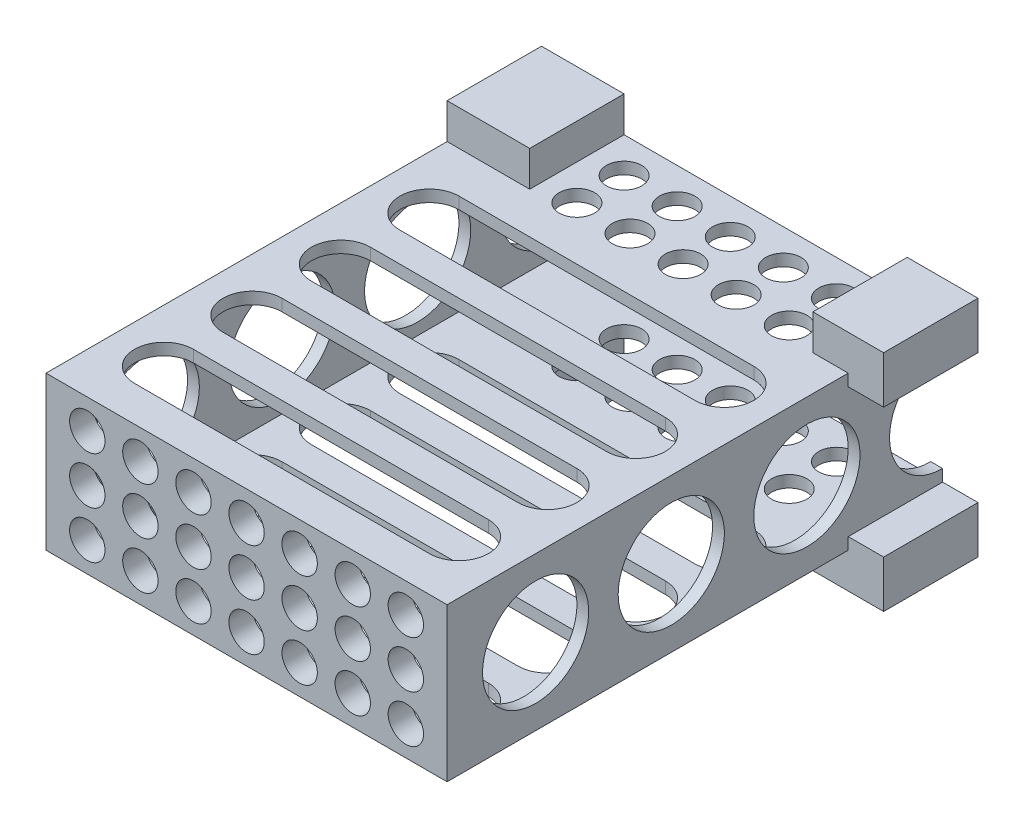
SolidWorks part; units mm, degrees
ref_plane "Přední rovina" through (0, 0, 0) normal (0, 0, 1) x (1, 0, 0)
ref_plane "Horní rovina" through (0, 0, 0) normal (0, 1, 0) x (1, 0, 0)
ref_plane "Pravá rovina" through (0, 0, 0) normal (1, 0, 0) x (0, 0, -1)
sketch "Skica1" plane through (0, 0, 0) normal (0, 0, 1) x (1, 0, 0)
  line L0 (0, 0) -> (0, 13) construction
  line L1 (0, 0) -> (34, 0) construction
  line L2 (-34, 13) -> (34, 13)
  line L3 (34, 13) -> (34, -13)
  line L4 (-34, -13) -> (34, -13)
  line L5 (-34, 13) -> (-34, -13)
  point P9 (0, -13)
  dimension "D1" = 68
  dimension "D2" = 26
extrude "Přidat vysunutím1" add sketch "Skica1" along normal blind 4
sketch "Skica2" plane through (0, 0, 0) normal (0, 0, -1) x (-1, 0, 0)
  line L0 (0, 0) -> (32, 0) construction
  line L1 (0, 0) -> (0, 11) construction
  line L2 (-32, 11) -> (32, 11)
  line L3 (32, 11) -> (32, -11)
  line L4 (-32, 11) -> (-32, -11)
  line L5 (-32, -11) -> (32, -11)
  line L6 (34, 13) -> (-34, 13)
  line L7 (-34, 13) -> (-34, -13)
  line L8 (-34, -13) -> (34, -13)
  line L9 (34, -13) -> (34, 13)
  point P11 (-32, 0)
  dimension "D1" = 2
  dimension "D2" = 2
extrude "Přidat vysunutím2" add sketch "Skica2" along normal blind 80
sketch "Skica7" plane through (0, 0, -80) normal (0, 0, 1) x (1, 0, 0)
  line L4 (0, 0) -> (34, 0) construction
  line L5 (32, 11) -> (34, 11) construction
  line L14 (3, 19) -> (40, 19)
  line L15 (40, 19) -> (40, 11)
  line L16 (40, 11) -> (34, 11)
  line L17 (34, 13) -> (34, -13) construction
  line L18 (34, 11) -> (34, 13)
  line L20 (3, 19) -> (-34, 19)
  line L21 (-34, 19) -> (-34, 13)
  line L22 (-32, 11) -> (32, 11) construction
  line L23 (34, 13) -> (-34, 13)
  line L25 (-34, -19) -> (-34, -13)
  line L26 (3, -19) -> (40, -19)
  line L27 (34, -13) -> (-34, -13)
  line L28 (34, -11) -> (34, -13)
  line L29 (40, -11) -> (34, -11)
  line L30 (40, -19) -> (40, -11)
  line L31 (3, -19) -> (-34, -19)
  dimension "D1" = 8
  dimension "D2" = 6
extrude "Přidat vysunutím9" add sketch "Skica7" along normal blind 16
sketch "Skica3" plane through (0, 0, -80) normal (0, 0, -1) x (-1, 0, 0)
  line L0 (0, 0) -> (-36, 0) construction
  line L1 (-36, 0) -> (-36, 15) construction
  line L2 (-4, 0) -> (-4, 15) construction
  circle A4 centre (-36, 15) radius 2
  circle A5 centre (28, 15) radius 2
  circle A6 centre (28, -15) radius 2
  circle A7 centre (-36, -15) radius 2
  dimension "D3" = 4
  dimension "D4" = 4
  dimension "D1" = 36
  dimension "D2" = 15
extrude "Odebrat vysunutím1" cut sketch "Skica3" against normal blind 15
sketch "Skica4" plane through (0, -13, 0) normal (0, -1, 0) x (1, 0, 0)
  line L0 (0, 0) -> (0, -52) construction
  line L1 (0, -52) -> (25, -52) construction
  line L2 (-25, -57) -> (25, -57)
  line L8 (-25, -47) -> (25, -47)
  line L9 (-25, -32) -> (25, -32)
  line L10 (-25, -42) -> (25, -42)
  line L11 (-25, -17) -> (25, -17)
  line L12 (-25, -27) -> (25, -27)
  line L13 (-25, -2) -> (25, -2)
  line L14 (-25, -12) -> (25, -12)
  arc A0 (25, -57) -> (25, -47) centre (25, -52) ccw
  arc A3 (-25, -57) -> (-25, -47) centre (-25, -52) cw
  arc A4 (25, -42) -> (25, -32) centre (25, -37) ccw
  arc A5 (-25, -42) -> (-25, -32) centre (-25, -37) cw
  arc A6 (25, -27) -> (25, -17) centre (25, -22) ccw
  arc A7 (-25, -27) -> (-25, -17) centre (-25, -22) cw
  arc A8 (25, -12) -> (25, -2) centre (25, -7) ccw
  arc A9 (-25, -12) -> (-25, -2) centre (-25, -7) cw
  dimension "D3" = 10
  dimension "D5" = 15
  dimension "D4" = 4
  dimension "D1" = 52
  dimension "D2" = 25
extrude "Odebrat vysunutím2" cut sketch "Skica4" against normal through all
sketch "Skica5" plane through (-34, 0, 0) normal (-1, 0, 0) x (0, 0, 1)
  line L0 (0, 0) -> (-80, 0) construction
  line L1 (-80, -19) -> (-80, 19) construction
  circle A0 centre (-80, 0) radius 9
  circle A1 centre (-57, 0) radius 9
  circle A2 centre (-34, 0) radius 9
  circle A3 centre (-11, 0) radius 9
  dimension "D1" = 18
  dimension "D3" = 23
  dimension "D2" = 4
extrude "Odebrat vysunutím3" cut sketch "Skica5" against normal through all
sketch "Skica8" plane through (0, 0, -80) normal (0, 0, -1) x (-1, 0, 0)
  line L0 (20, 19) -> (20, 13)
  line L1 (-40, 19) -> (34, 19) construction
  line L3 (20, 13) -> (-28, 13)
  line L5 (-28, 13) -> (-28, 19)
  line L6 (-28, 19) -> (20, 19)
  line L7 (0, 0) -> (14.4774, 0) construction
  line L8 (-28, -13) -> (-28, -19)
  line L9 (20, -13) -> (-28, -13)
  line L10 (20, -19) -> (20, -13)
  line L11 (-28, -19) -> (20, -19)
  line L12 (32, 11) -> (-32, 11) construction
  circle A0 centre (28, 15) radius 2 construction
  circle A1 centre (-36, 15) radius 2 construction
  dimension "D1" = 8
  dimension "D2" = 8
  dimension "D3" = 2
extrude "Odebrat vysunutím4" cut sketch "Skica8" against normal blind 16
sketch "Skica9" plane through (0, 0, 4) normal (0, 0, 1) x (1, 0, 0)
  line L0 (0, 0) -> (-27, 0) construction
  line L1 (-27, 0) -> (-27, 8) construction
  circle A0 centre (-27, 8) radius 3
  circle A1 centre (-18, 8) radius 3
  circle A2 centre (-9, 8) radius 3
  circle A3 centre (0, 8) radius 3
  circle A4 centre (9, 8) radius 3
  circle A5 centre (18, 8) radius 3
  circle A6 centre (27, 8) radius 3
  circle A7 centre (-18, 0) radius 3
  circle A8 centre (-9, 0) radius 3
  circle A9 centre (0, 0) radius 3
  circle A10 centre (9, 0) radius 3
  circle A11 centre (18, 0) radius 3
  circle A12 centre (27, 0) radius 3
  circle A13 centre (-18, -8) radius 3
  circle A14 centre (-9, -8) radius 3
  circle A15 centre (0, -8) radius 3
  circle A16 centre (9, -8) radius 3
  circle A17 centre (18, -8) radius 3
  circle A18 centre (27, -8) radius 3
  circle A19 centre (-27, 0) radius 3
  circle A20 centre (-27, -8) radius 3
  dimension "D2" = 6
  dimension "D1" = 27
  dimension "D3" = 8
  dimension "D6" = 9
  dimension "D7" = 8
  dimension "D8" = 8
  dimension "D4" = 7
  dimension "D5" = 3
extrude "Odebrat vysunutím5" cut sketch "Skica9" against normal blind 4
sketch "Skica10" plane through (0, 13, 0) normal (0, 1, 0) x (1, 0, 0)
  line L0 (4, 80) -> (4, 74) construction
  line L1 (28, 80) -> (-20, 80) construction
  line L2 (4, 74) -> (-14, 74) construction
  line L3 (-14, 66) -> (-14, 74) construction
  circle A0 centre (-14, 74) radius 3
  circle A1 centre (-5, 74) radius 3
  circle A2 centre (4, 74) radius 3
  circle A3 centre (13, 74) radius 3
  circle A4 centre (22, 74) radius 3
  circle A5 centre (-5, 66) radius 3
  circle A6 centre (4, 66) radius 3
  circle A7 centre (13, 66) radius 3
  circle A8 centre (22, 66) radius 3
  circle A9 centre (-14, 66) radius 3
  dimension "D2" = 6
  dimension "D1" = 6
  dimension "D3" = 18
  dimension "D6" = 9
  dimension "D7" = 8
  dimension "D4" = 5
  dimension "D5" = 2
extrude "Odebrat vysunutím6" cut sketch "Skica10" against normal through all
